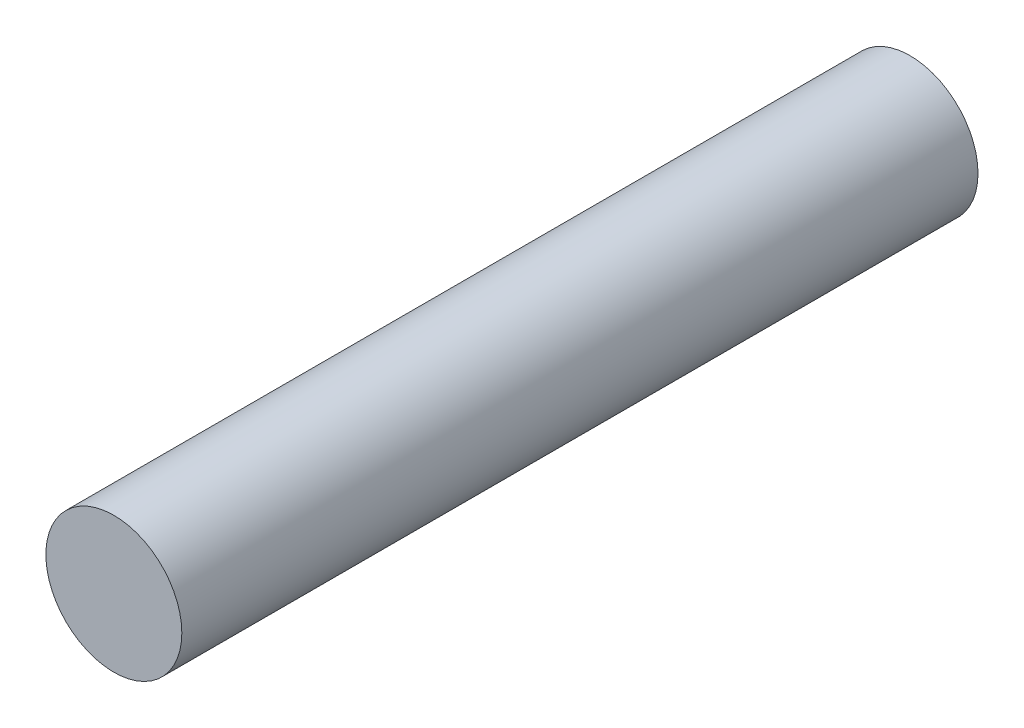
SolidWorks part; units mm, degrees
material "素碳鋼"
ref_plane "前基準面" through (0, 0, 0) normal (0, 0, 1) x (1, 0, 0)
ref_plane "上基準面" through (0, 0, 0) normal (0, 1, 0) x (1, 0, 0)
ref_plane "右基準面" through (0, 0, 0) normal (1, 0, 0) x (0, 0, -1)
sketch "草圖1" plane through (0, 0, 0) normal (0, 0, 1) x (1, 0, 0)
  circle A0 centre (0, 0) radius 11.1
  dimension "D1" = 22.2
extrude "伸長1" add sketch "草圖1" along normal mid plane 130
